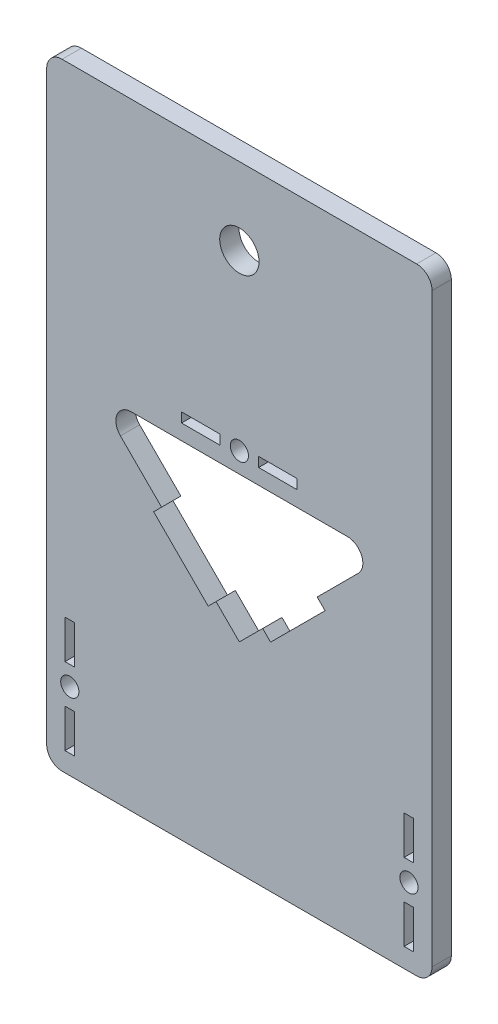
SolidWorks part; units mm, degrees
ref_plane "Front Plane" through (0, 0, 0) normal (0, 0, 1) x (1, 0, 0)
ref_plane "Top Plane" through (0, 0, 0) normal (0, 1, 0) x (1, 0, 0)
ref_plane "Right Plane" through (0, 0, 0) normal (1, 0, 0) x (0, 0, -1)
sketch "Sketch1" plane through (0, 0, 0) normal (0, 0, 1) x (1, 0, 0)
  line L0 (31.75, 63.5) -> (31.75, 0) construction
  line L1 (0, 0) -> (63.5, 0)
  line L2 (0, 0) -> (0, 63.5)
  line L3 (0, 63.5) -> (63.5, 63.5)
  line L4 (63.5, 0) -> (63.5, 63.5)
  line L5 (0, 31.75) -> (63.5, 31.75) construction
  line L6 (0, 63.5) -> (31.75, 31.75) construction
  line L7 (31.75, 31.75) -> (63.5, 63.5) construction
  line L8 (17.6285, 44.5693) -> (18.9307, 45.8715)
  line L9 (18.9307, 45.8715) -> (27.9109, 36.8912)
  line L10 (27.9109, 36.8912) -> (26.6088, 35.5891)
  line L11 (26.6088, 35.5891) -> (17.6285, 44.5693)
  line L12 (18.2796, 45.2204) -> (27.2599, 36.2401) construction
  line L13 (27.9109, 36.8912) -> (18.9307, 45.8715)
  line L14 (17.6285, 44.5693) -> (26.6088, 35.5891)
  line L15 (45.2204, 45.2204) -> (36.2401, 36.2401) construction
  line L16 (45.8715, 44.5693) -> (36.8912, 35.5891)
  line L17 (35.5891, 36.8912) -> (44.5693, 45.8715)
  line L18 (36.8912, 35.5891) -> (45.8715, 44.5693)
  line L19 (35.5891, 36.8912) -> (36.8912, 35.5891)
  line L20 (44.5693, 45.8715) -> (35.5891, 36.8912)
  line L21 (45.8715, 44.5693) -> (44.5693, 45.8715)
  line L22 (31.75, 63.5) -> (31.75, 96.6607) construction
  line L24 (63.5, 63.5) -> (0, 63.5)
  line L25 (63.5, 63.5) -> (63.5, 101.6)
  line L26 (63.5, 101.6) -> (0, 101.6)
  line L27 (0, 60.325) -> (63.5, 60.325) construction
  line L28 (41.275, 59.5313) -> (34.925, 61.1187) construction
  line L29 (22.225, 61.1188) -> (28.575, 61.1187)
  line L30 (22.225, 61.1188) -> (22.225, 59.5313)
  line L31 (22.225, 59.5313) -> (28.575, 59.5313)
  line L32 (28.575, 61.1187) -> (28.575, 59.5313)
  line L33 (22.225, 61.1188) -> (28.575, 59.5313) construction
  line L34 (22.225, 59.5313) -> (28.575, 61.1187) construction
  line L35 (41.275, 61.1188) -> (34.925, 59.5313) construction
  line L36 (34.925, 61.1187) -> (34.925, 59.5313)
  line L37 (41.275, 59.5313) -> (34.925, 59.5313)
  line L38 (41.275, 61.1188) -> (41.275, 59.5313)
  line L39 (41.275, 61.1188) -> (34.925, 61.1187)
  line L40 (0, 63.5) -> (0, 101.6)
  circle A0 centre (31.75, 88.9) radius 3.2385
  circle A1 centre (31.75, 88.9) radius 5.08
  circle A2 centre (31.75, 60.325) radius 1.5
  point P34 (25.4, 60.325)
  point P45 (38.1, 60.325)
  dimension "D6" = 6.477
  dimension "D7" = 10.16
  dimension "D14" = 3
  dimension "D1" = 63.5
  dimension "D2" = 63.5
  dimension "D3" = 1.8415
  dimension "D4" = 12.7
  dimension "D5" = 6.35
  dimension "D8" = 25.4
  dimension "D9" = 38.1
  dimension "D11" = 3.175
  dimension "D12" = 1.5875
  dimension "D13" = 6.35
  dimension "D15" = 6.35
extrude "Boss-Extrude1" add sketch "Sketch1" along normal blind 3.175
sketch "Sketch2" plane through (0, 0, 3.175) normal (0, 0, 1) x (1, 0, 0)
  line L0 (27.9109, 36.8912) -> (31.75, 33.0521)
  line L1 (35.5891, 36.8912) -> (31.75, 33.0521)
  line L2 (7.8109, 56.9913) -> (55.6891, 56.9913)
  line L3 (27.9109, 36.8912) -> (18.9307, 45.8715)
  line L4 (18.9307, 45.8715) -> (7.8109, 56.9913)
  line L5 (35.5891, 36.8912) -> (44.5693, 45.8715)
  line L6 (44.5693, 45.8715) -> (55.6891, 56.9913)
  line L7 (22.225, 59.5313) -> (28.575, 59.5313) construction
  dimension "D1" = 2.54
extrude "Cut-Extrude1" cut sketch "Sketch2" against normal blind 3.175
sketch "Sketch3" plane through (0, 0, 3.175) normal (0, 0, 1) x (1, 0, 0)
  line L0 (31.75, 0) -> (31.75, 33.0521) construction
  line L1 (0, 0) -> (63.5, 0) construction
  line L2 (3.81, 0) -> (3.81, 24.1416) construction
  line L3 (0, 0) -> (0, 101.6) construction
  line L4 (60.4837, 3.175) -> (58.8962, 9.525) construction
  line L5 (3.0162, 22.225) -> (4.6037, 22.225)
  line L6 (3.0162, 22.225) -> (3.0163, 15.875)
  line L7 (3.0163, 15.875) -> (4.6037, 15.875)
  line L8 (4.6037, 22.225) -> (4.6037, 15.875)
  line L9 (3.0162, 22.225) -> (4.6037, 15.875) construction
  line L10 (3.0163, 15.875) -> (4.6037, 22.225) construction
  line L11 (3.0162, 9.525) -> (4.6037, 9.525)
  line L12 (3.0162, 9.525) -> (3.0163, 3.175)
  line L13 (3.0163, 3.175) -> (4.6037, 3.175)
  line L14 (4.6037, 9.525) -> (4.6037, 3.175)
  line L15 (3.0162, 9.525) -> (4.6037, 3.175) construction
  line L16 (3.0163, 3.175) -> (4.6037, 9.525) construction
  line L17 (60.4837, 9.525) -> (58.8962, 3.175) construction
  line L18 (60.4837, 15.875) -> (58.8962, 22.225) construction
  line L19 (60.4837, 22.225) -> (58.8962, 15.875) construction
  line L20 (58.8962, 9.525) -> (58.8962, 3.175)
  line L21 (60.4837, 3.175) -> (58.8962, 3.175)
  line L22 (60.4837, 9.525) -> (60.4837, 3.175)
  line L23 (60.4837, 9.525) -> (58.8962, 9.525)
  line L24 (58.8962, 22.225) -> (58.8962, 15.875)
  line L25 (60.4837, 15.875) -> (58.8962, 15.875)
  line L26 (60.4837, 22.225) -> (60.4837, 15.875)
  line L27 (60.4837, 22.225) -> (58.8962, 22.225)
  circle A0 centre (3.81, 12.7) radius 1.5
  circle A1 centre (59.69, 12.7) radius 1.5
  point P9 (3.81, 19.05)
  point P14 (3.81, 6.35)
  point P31 (59.69, 6.35)
  point P32 (59.69, 19.05)
  dimension "D7" = 3
  dimension "D1" = 3.81
  dimension "D2" = 6.35
  dimension "D3" = 1.5875
  dimension "D4" = 3.175
  dimension "D5" = 3.175
  dimension "D6" = 6.35
extrude "Cut-Extrude2" cut sketch "Sketch3" against normal blind 3.175
fillet "Fillet1" radius 2.54 6 edges at (0, 101.6, 1.5875) (63.5, 101.6, 1.5875) (63.5, 0, 1.5875) (0, 0, 1.5875) (55.6891, 56.9913, 1.5875) (7.8109, 56.9913, 1.5875)
